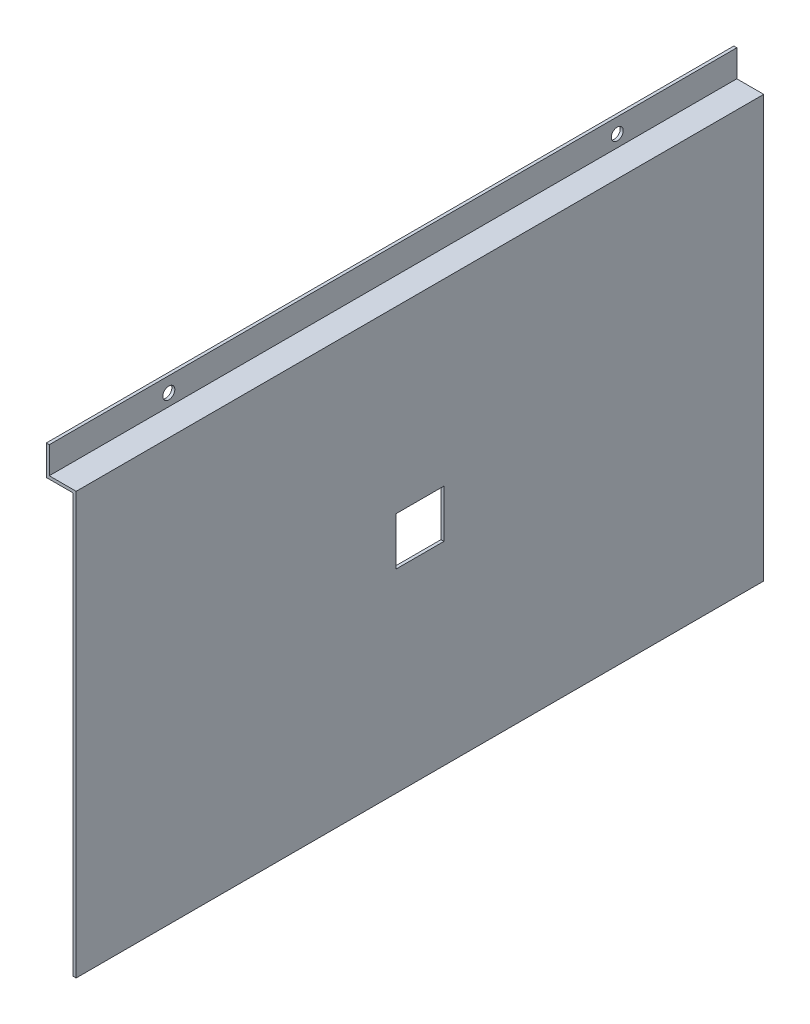
SolidWorks part; units mm, degrees
ref_plane "Alzado" through (0, 0, 0) normal (0, 0, 1) x (1, 0, 0)
ref_plane "Planta" through (0, 0, 0) normal (0, 1, 0) x (1, 0, 0)
ref_plane "Vista lateral" through (0, 0, 0) normal (1, 0, 0) x (0, 0, -1)
sketch "Croquis1" plane through (0, 0, 0) normal (0, 0, 1) x (1, 0, 0)
  line L0 (-38.1189, 44.5866) -> (-38.1189, 34.5866)
  line L1 (-38.1189, 34.5866) -> (-29.1189, 34.5866)
  line L2 (-29.1189, 34.5866) -> (-29.1189, -105.4134)
extrude "Extruir-Lámina1" add sketch "Croquis1" along normal blind 230 thin thin type one direction reverse wall 1
sketch "Croquis2" plane through (-37.1189, 0, 0) normal (1, 0, 0) x (0, 0, -1)
  line L0 (0, 44.5866) -> (0, 34.5866) construction
  line L1 (-230, 44.5866) -> (0, 44.5866) construction
  line L2 (-230, 44.5866) -> (-230, 35.5866) construction
  circle A0 centre (-190, 39.5866) radius 2
  circle A1 centre (-40, 39.5866) radius 2
  point P4 (0, 39.5866)
  dimension "D1" = 40
  dimension "D2" = 5
  dimension "D3" = 5
  dimension "D4" = 40
extrude "Cortar-Extruir1" cut sketch "Croquis2" against normal up to surface (1 mm away) up to face at (-38.1189, 39.5866, 115)
sketch "Croquis3" plane through (-28.1189, 0, 0) normal (1, 0, 0) x (0, 0, -1)
  line L0 (-230, 35.5866) -> (0, 35.5866) construction
  line L1 (-123.013, -40.4394) -> (-106.987, -40.4394)
  line L2 (-123.013, -40.4394) -> (-123.013, -24.4134)
  line L3 (-123.013, -24.4134) -> (-106.987, -24.4134)
  line L4 (-106.987, -40.4394) -> (-106.987, -24.4134)
  line L5 (-123.013, -40.4394) -> (-106.987, -24.4134) construction
  line L6 (-123.013, -24.4134) -> (-106.987, -40.4394) construction
  line L8 (0, 35.5866) -> (0, -105.4134) construction
  point P0 (-115, -32.4264)
  point P7 (0, -34.9134)
  dimension "D1" = 60
  dimension "D2" = 115
extrude "Cortar-Extruir2" cut sketch "Croquis3" against normal up to surface (1 mm away) up to face at (-29.1189, -35.4134, 115)
